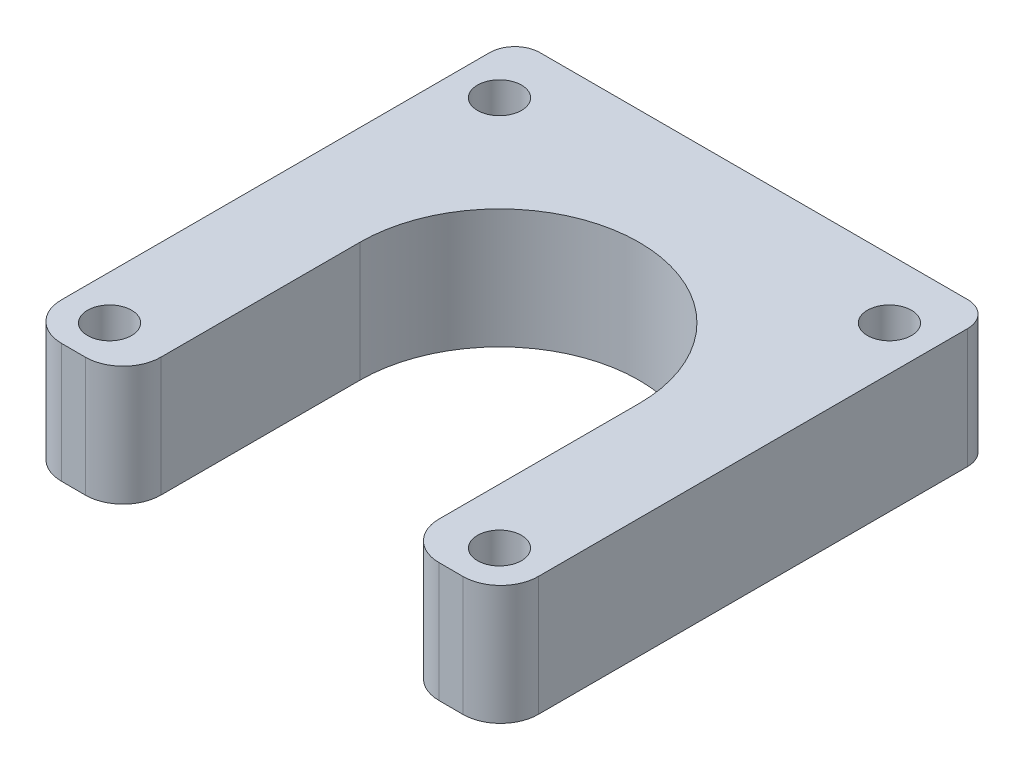
SolidWorks part; units mm, degrees
ref_plane "Alzado" through (0, 0, 0) normal (0, 0, 1) x (1, 0, 0)
ref_plane "Planta" through (0, 0, 0) normal (0, 1, 0) x (1, 0, 0)
ref_plane "Vista lateral" through (0, 0, 0) normal (1, 0, 0) x (0, 0, -1)
sketch "Croquis1" plane through (0, 0, 0) normal (0, 1, 0) x (1, 0, 0)
  line L0 (16.5, -9.9941) -> (16.5, -10.6274)
  line L1 (-13.6, 5.2837) -> (-13.6, -10.5387)
  line L2 (8.6, 5.2837) -> (8.6, -10.6218)
  line L3 (11.5912, -13.6218) -> (13.4912, -13.6274)
  line L12 (16.5, -7.9887) -> (16.5, 23.5)
  line L13 (14.5, 25.5) -> (-19.5, 25.5)
  line L14 (-21.5, 23.5) -> (-21.5, -10.5331)
  line L27 (16.5, -7.9887) -> (16.5, -9.9941)
  line L31 (-18.5088, -13.5331) -> (-16.6088, -13.5387)
  arc A0 (13.4912, -13.6274) -> (16.5, -10.6274) centre (13.5, -10.6274) ccw
  arc A1 (-18.5088, -13.5331) -> (-21.5, -10.5331) centre (-18.5, -10.5331) cw
  arc A2 (11.5912, -13.6218) -> (8.6, -10.6218) centre (11.6, -10.6218) cw
  arc A3 (-16.6088, -13.5387) -> (-13.6, -10.5387) centre (-16.6, -10.5387) ccw
  arc A8 (16.5, 23.5) -> (14.5, 25.5) centre (14.5, 23.5) ccw
  arc A9 (-19.5, 25.5) -> (-21.5, 23.5) centre (-19.5, 23.5) ccw
  arc A18 (8.6, 5.2837) -> (-13.6, 5.2837) centre (-2.5, 5.2837) ccw
  circle A19 centre (-18, -10.2163) radius 1.75
  circle A20 centre (-18, 20.7837) radius 1.75
  circle A21 centre (13, -10.2163) radius 1.75
  circle A22 centre (13, 20.7837) radius 1.75
  point P12 (8.6, -13.613)
  dimension "D1" = 3
  dimension "D2" = 3
  dimension "D3" = 3.5
  dimension "D4" = 3.5
  dimension "D5" = 3.5
  dimension "D6" = 3.5
extrude "Saliente-Extruir1" add sketch "Croquis1" along normal blind 9.5
